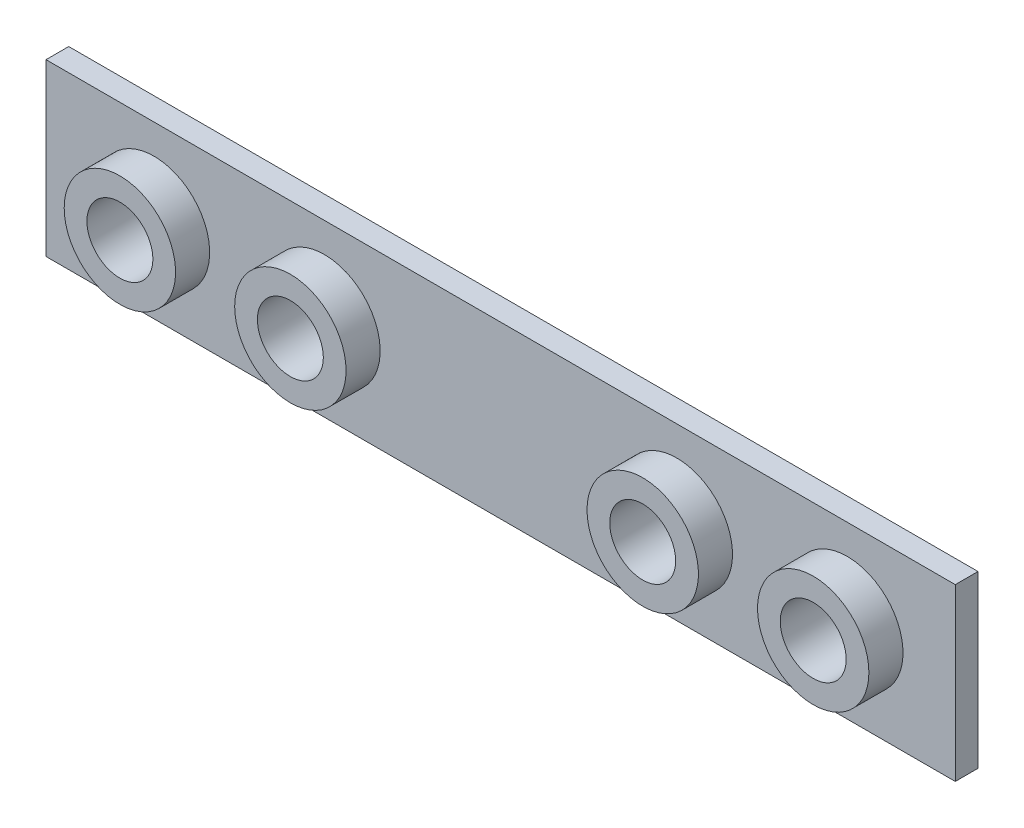
SolidWorks part; units mm, degrees
ref_plane "Front Plane" through (0, 0, 0) normal (0, 0, 1) x (1, 0, 0)
ref_plane "Top Plane" through (0, 0, 0) normal (0, 1, 0) x (1, 0, 0)
ref_plane "Right Plane" through (0, 0, 0) normal (1, 0, 0) x (0, 0, -1)
sketch "Sketch1" plane through (0, 0, 0) normal (0, 0, 1) x (1, 0, 0)
  line L0 (-23, 0) -> (23, 0) construction
  line L1 (0, 22.8395) -> (0, -24.8721) construction
  line L2 (-23, 12.8907) -> (-23, -21.4488) construction
  circle A0 centre (-15.5, 0) radius 2.9
  circle A1 centre (-30.5, 0) radius 2.9
  circle A2 centre (30.5, 0) radius 2.9
  circle A3 centre (15.5, 0) radius 2.9
  circle A4 centre (-15.5, 0) radius 4.9
  circle A5 centre (-30.5, 0) radius 4.9
  circle A6 centre (15.5, 0) radius 4.9
  circle A7 centre (30.5, 0) radius 4.9
  point P3 (0, 0)
  dimension "D2" = 5.8
  dimension "D4" = 9.8
  dimension "D1" = 46
  dimension "D3" = 7.5
extrude "Boss-Extrude1" add sketch "Sketch1" along normal blind 5
sketch "Sketch3" plane through (0, 0, 0) normal (0, 0, 1) x (1, 0, 0)
  line L1 (-40, -7.5) -> (40, -7.5)
  line L2 (-40, -7.5) -> (-40, 7.5)
  line L3 (-40, 7.5) -> (40, 7.5)
  line L4 (40, -7.5) -> (40, 7.5)
  line L5 (-40, -7.5) -> (40, 7.5) construction
  line L6 (-40, 7.5) -> (40, -7.5) construction
  point P0 (0, 0)
  dimension "D1" = 80
  dimension "D2" = 15
extrude "Boss-Extrude2" add sketch "Sketch3" along normal blind 2
sketch "Sketch4" plane through (0, 0, 5) normal (0, 0, 1) x (1, 0, 0)
  circle A0 centre (-30.5, 0) radius 2.9
  circle A1 centre (-15.5, 0) radius 2.9
  circle A2 centre (15.5, 0) radius 2.9
  circle A3 centre (30.5, 0) radius 2.9
  circle A4 centre (-30.5, 0) radius 2.9 construction
  circle A5 centre (-15.5, 0) radius 2.9 construction
  circle A6 centre (15.5, 0) radius 2.9 construction
  circle A7 centre (30.5, 0) radius 2.9 construction
extrude "Cut-Extrude1" cut sketch "Sketch4" against normal through all
